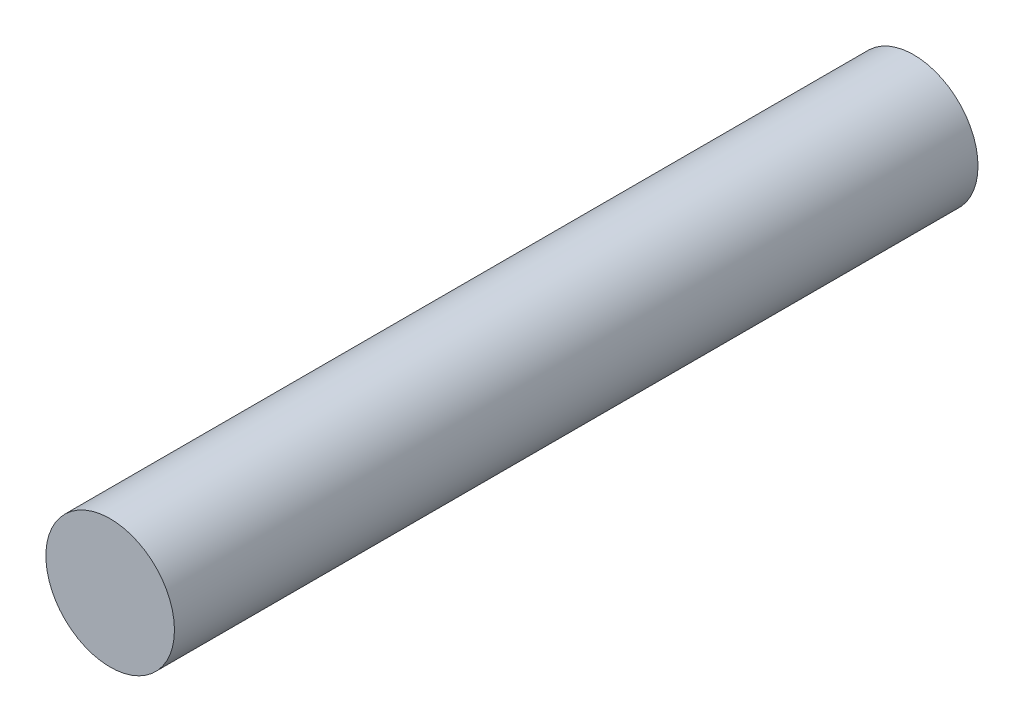
SolidWorks part; units mm, degrees
ref_plane "Front Plane" through (0, 0, 0) normal (0, 0, 1) x (1, 0, 0)
ref_plane "Top Plane" through (0, 0, 0) normal (0, 1, 0) x (1, 0, 0)
ref_plane "Right Plane" through (0, 0, 0) normal (1, 0, 0) x (0, 0, -1)
sketch "Sketch1" plane through (0, 0, 0) normal (0, 0, 1) x (1, 0, 0)
  circle A0 centre (0, 0) radius 2.4
  dimension "D1" = 4.8
extrude "Boss-Extrude1" add sketch "Sketch1" along normal blind 30
